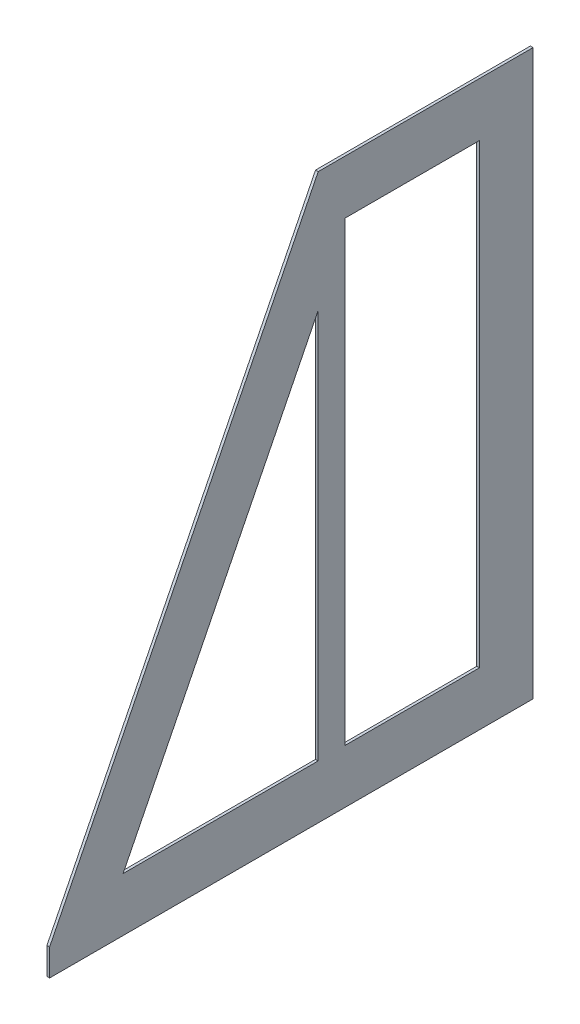
SolidWorks part; units mm, degrees
ref_plane "Front Plane" through (0, 0, 0) normal (0, 0, 1) x (1, 0, 0)
ref_plane "Top Plane" through (0, 0, 0) normal (0, 1, 0) x (1, 0, 0)
ref_plane "Right Plane" through (0, 0, 0) normal (1, 0, 0) x (0, 0, -1)
sketch "Sketch1" plane through (0, 0, 0) normal (1, 0, 0) x (0, 0, -1)
  line L9 (-67.4659, 387.2426) -> (135.7341, 387.2426)
  line L10 (135.7341, 387.2426) -> (135.7341, -146.1574)
  line L11 (135.7341, -146.1574) -> (-321.4659, -146.1574)
  line L12 (-321.4659, -146.1574) -> (-321.4659, -120.7574)
  line L13 (-321.4659, -120.7574) -> (-67.4659, 387.2426)
  line L14 (84.9341, 336.4426) -> (84.9341, -95.3574)
  line L15 (84.9341, -95.3574) -> (-42.0659, -95.3574)
  line L16 (-42.0659, -95.3574) -> (-42.0659, 336.4426)
  line L17 (-42.0659, 336.4426) -> (84.9341, 336.4426)
  line L21 (-67.4659, 273.6503) -> (-251.9698, -95.3574)
  line L22 (-251.9698, -95.3574) -> (-67.4659, -95.3574)
  line L23 (-67.4659, -95.3574) -> (-67.4659, 273.6503)
  dimension "D1" = 457.2
  dimension "D2" = 533.4
  dimension "D3" = 203.2
  dimension "D4" = 50.8
  dimension "D5" = 50.8
  dimension "D6" = 50.8
  dimension "D7" = 25.4
  dimension "D8" = 50.8
  dimension "D9" = 25.4
  dimension "D10" = 567.9613
  dimension "D11" = 25.4
  dimension "D12" = 50.8
extrude "Boss-Extrude1" add sketch "Sketch1" along normal blind 2.54
